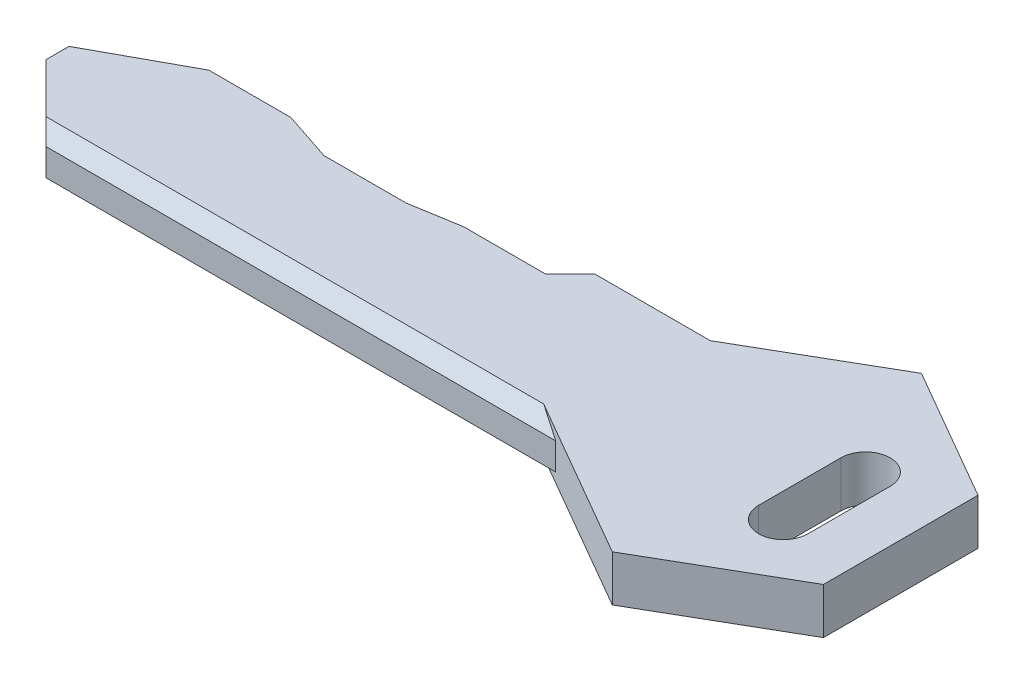
SolidWorks part; units mm, degrees
ref_plane "Front Plane" through (0, 0, 0) normal (0, 0, 1) x (1, 0, 0)
ref_plane "Top Plane" through (0, 0, 0) normal (0, 1, 0) x (1, 0, 0)
ref_plane "Right Plane" through (0, 0, 0) normal (1, 0, 0) x (0, 0, -1)
sketch "Sketch1" plane through (0, 0, 0) normal (0, 1, 0) x (1, 0, 0)
  line L0 (43.1406, 4.7) -> (46.6406, 4.7) construction
  line L1 (0, 0) -> (35, 0)
  line L2 (0, 0) -> (0, 9.4)
  line L3 (0, 9.4) -> (35, 9.4)
  line L4 (35, 0) -> (35, 9.4)
  line L5 (43.1406, -4.7) -> (51.2813, 0)
  line L6 (51.2813, 0) -> (51.2813, 9.4)
  line L7 (51.2813, 9.4) -> (43.1406, 14.1)
  line L8 (43.1406, 14.1) -> (35, 9.4)
  line L9 (35, 9.4) -> (35, 0)
  line L10 (35, 0) -> (43.1406, -4.7)
  line L11 (46.6406, 4.7) -> (46.6406, 7.2) construction
  line L12 (46.6406, 4.7) -> (46.6406, 2.2) construction
  line L13 (46.6406, 7.2) -> (46.6406, 2.2) construction
  line L14 (48.1406, 7.2) -> (48.1406, 2.2)
  line L15 (45.1406, 7.2) -> (45.1406, 2.2)
  circle A0 centre (43.1406, 4.7) radius 8.1406 construction
  arc A1 (48.1406, 7.2) -> (45.1406, 7.2) centre (46.6406, 7.2) ccw
  arc A2 (45.1406, 2.2) -> (48.1406, 2.2) centre (46.6406, 2.2) ccw
  point P1 (46.6406, 4.7)
  dimension "D1" = 35
  dimension "D2" = 9.4
  dimension "D3" = 5
  dimension "D4" = 3
  dimension "D5" = 3.5
extrude "Boss-Extrude1" add sketch "Sketch1" along normal blind 2.8 contours L1 L4 L3 L2 | L4 L10 L5 L6 L7 L8 A2 L15 A1 L14
sketch "Sketch2" plane through (0, 0, 0) normal (-1, 0, 0) x (0, 0, 1)
  line L0 (0, 0) -> (-9.4, 0) construction
  line L1 (-6, 0) -> (-2.9, 0)
  line L2 (-6, 0) -> (-6, 1.6)
  line L3 (-6, 1.6) -> (-2.9, 1.6)
  line L4 (-2.9, 0) -> (-2.9, 1.6)
  line L6 (-2.9, 1.6) -> (0, 1.6) construction
  line L7 (0, 2.8) -> (0, 0) construction
  line L8 (-6, 1.6) -> (-9.4, 1.6) construction
  line L10 (-9.4, 2.8) -> (-9.4, 0) construction
  dimension "D1" = 3.4
  dimension "D2" = 2.9
  dimension "D3" = 90
  dimension "D4" = 3.1
  dimension "D5" = 1.6
extrude "Cut-Extrude1" cut sketch "Sketch2" against normal blind 35
chamfer "Chamfer2" distance 4 angle 45 1 edges at (0, 1.4, 0)
sketch "Sketch3" plane through (0, 2.8, 0) normal (0, 1, 0) x (1, 0, 0)
  line L0 (35, 9.4) -> (24, 9.4) construction
  line L1 (0, 9.4) -> (35, 9.4) construction
  line L2 (24, 9.4) -> (16, 9.4) construction
  line L3 (16, 9.4) -> (8, 9.4) construction
  line L4 (8, 9.4) -> (8, 8.4) construction
  line L5 (16, 9.4) -> (16, 7.4) construction
  line L6 (24, 9.4) -> (24, 7.9) construction
  line L7 (8, 8.4) -> (10.5, 8.4)
  line L10 (13.5, 7.4) -> (16, 7.4)
  line L11 (16, 7.4) -> (18.5, 7.4)
  line L14 (21.5, 7.9) -> (24, 7.9)
  line L15 (24, 7.9) -> (26.5, 7.9)
  line L16 (26.5, 7.9) -> (28, 9.4)
  line L17 (8, 8.4) -> (5.5, 8.4)
  line L18 (8, 9.4) -> (4, 9.4) construction
  line L20 (4, 9.4) -> (28, 9.4)
  line L21 (21.5, 7.9) -> (18.5, 7.4)
  line L22 (10.5, 8.4) -> (13.5, 7.4)
  line L25 (5.5, 8.4) -> (0, 5.4)
  line L26 (0, 4) -> (0, 9.4) construction
  line L27 (0, 5.4) -> (0, 9.4)
  line L28 (0, 9.4) -> (4, 9.4)
  dimension "D1" = 11
  dimension "D2" = 8
  dimension "D3" = 8
  dimension "D4" = 4
  dimension "D5" = 2.5
  dimension "D6" = 1
  dimension "D7" = 2
  dimension "D8" = 1.5
  dimension "D9" = 4
  dimension "D10" = 4
chamfer "Chamfer5" distance 1 angle 30 1 edges at (19.5, 0, 0)
chamfer "Chamfer6" distance 1 angle 30 1 edges at (19.5, 2.8, 0)
extrude "Cut-Extrude2" cut sketch "Sketch3" against normal blind 10
